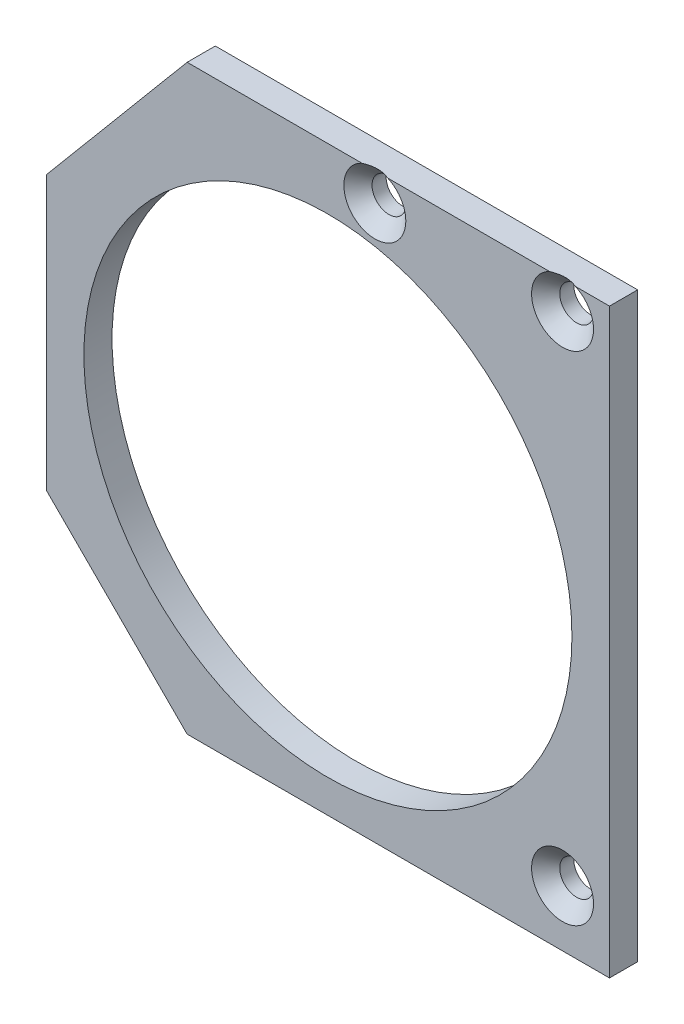
SolidWorks part; units mm, degrees
material "Hexcel AS4C (3000 丝)"
ref_plane "前视基准面" through (0, 0, 0) normal (0, 0, 1) x (1, 0, 0)
ref_plane "上视基准面" through (0, 0, 0) normal (0, 1, 0) x (1, 0, 0)
ref_plane "右视基准面" through (0, 0, 0) normal (1, 0, 0) x (0, 0, -1)
sketch "草图1" plane through (0, 0, 0) normal (0, 0, 1) x (1, 0, 0)
  line L0 (0, 31) -> (0, -31) construction
  line L1 (-30, 31) -> (30, 31)
  line L2 (-30, 31) -> (-30, -31)
  line L3 (-30, -31) -> (30, -31)
  line L4 (30, 31) -> (30, -31)
  line L5 (-30, 31) -> (30, -31) construction
  line L6 (-30, -31) -> (30, 31) construction
  line L7 (5, 28) -> (25, 28) construction
  circle A1 centre (0, -1.5) radius 26
  circle A2 centre (25, 28) radius 1.6
  circle A3 centre (5, 28) radius 1.6
  point P0 (0, 0)
  dimension "D3" = 20
  dimension "D4" = 3.2
  dimension "D5" = 3
  dimension "D6" = 5
  dimension "D7" = 52
  dimension "D8" = 5
  dimension "D9" = 29.5
  dimension "D1" = 62
  dimension "D2" = 60
extrude "凸台-拉伸1" add sketch "草图1" along normal blind 3
sketch "草图2" plane through (0, 0, 3) normal (0, 0, 1) x (1, 0, 0)
  line L0 (-30, 13.1237) -> (-15, 31)
  line L1 (0, 0) -> (-30, 0) construction
  line L2 (-30, 31) -> (-30, -31) construction
  line L4 (30, -31) -> (30, 31)
  line L5 (30, 31) -> (-30, 31)
  line L6 (-30, 31) -> (-30, -31)
  line L7 (-30, -31) -> (30, -31)
  line L9 (-15, 31) -> (-30, 31)
  line L10 (-30, 31) -> (-30, 13.1237)
  dimension "D2" = 50
  dimension "D3" = 15
  dimension "D1" = 0
extrude "切除-拉伸1" cut sketch "草图2" against normal through all contours L9 L10 L0
sketch "草图4" plane through (0, 0, 3) normal (0, 0, 1) x (1, 0, 0)
  line L0 (-30, -16) -> (-15, -31)
  line L1 (-30, 13.1237) -> (-30, -31) construction
  line L2 (-30, -31) -> (30, -31) construction
  line L8 (-15, 31) -> (-30, 13.1237)
  line L9 (-30, 13.1237) -> (-30, -31)
  line L10 (-30, -31) -> (30, -31)
  line L11 (30, -31) -> (30, 31)
  line L12 (30, 31) -> (-15, 31)
  line L14 (-30, -16) -> (-30, -31)
  line L15 (-30, -31) -> (-15, -31)
  dimension "D2" = 15
  dimension "D3" = 15
  dimension "D1" = 0
extrude "切除-拉伸2" cut sketch "草图4" against normal up to next
sketch "草图5" plane through (0, 0, 3) normal (0, 0, 1) x (1, 0, 0)
  line L0 (-15, -31) -> (30, -31) construction
  line L1 (30, -31) -> (30, 31) construction
  circle A0 centre (25, -25) radius 1.6
  dimension "D1" = 6
  dimension "D2" = 3.2
  dimension "D3" = 5
extrude "切除-拉伸3" cut sketch "草图5" against normal through all
hole_wizard "M3 十字槽半沉头木螺钉的锥形沉头孔1" positions "草图6" profile "草图7" countersink size "M3" standard "GB" end condition through all
sketch "草图6" plane through (0, 0, 3) normal (0, 0, 1) x (1, 0, 0)
  point P0 (5, 28)
  point P3 (25, 28)
  point P6 (25, -25)
sketch "草图7" plane through (5, 28, 3) normal (1, 0, 0) x (0, -1, 0)
  line L0 (0, 0) -> (0, 3)
  line L1 (0, 3) -> (1.8, 3)
  line L2 (1.8, 3) -> (1.8, 1.5)
  line L3 (1.8, 1.5) -> (3.3, 0)
  line L5 (3.3, 0) -> (0, 0)
  line L6 (-1.8, 1.5) -> (-3.3, 0) construction
  line L11 (0, -6.35) -> (0, 107.95) construction
  dimension "通孔孔直径" = 3.6
  dimension "通孔孔深度" = 3
  dimension "近端锥形沉头孔直径" = 6.6
  dimension "近端锥形沉头孔角度" = 90
